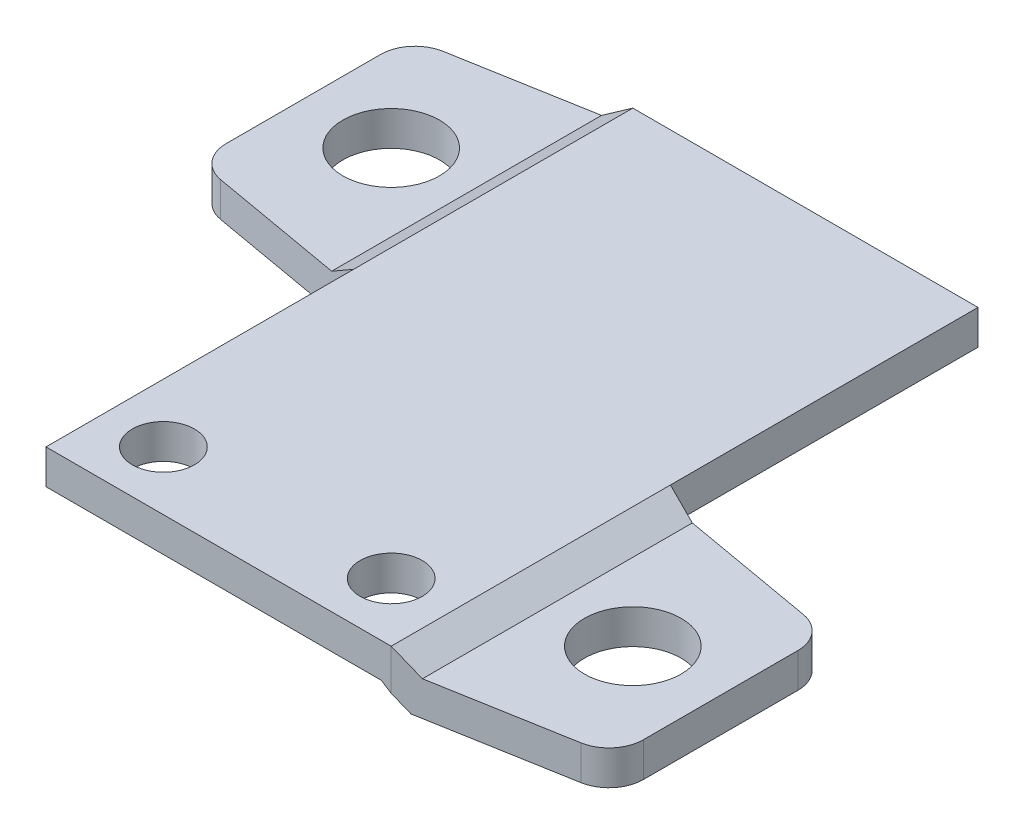
SolidWorks part; units mm, degrees
ref_plane "Front Plane" through (0, 0, 0) normal (0, 0, 1) x (1, 0, 0)
ref_plane "Top Plane" through (0, 0, 0) normal (0, 1, 0) x (1, 0, 0)
ref_plane "Right Plane" through (0, 0, 0) normal (1, 0, 0) x (0, 0, -1)
sketch "Sketch1" plane through (0, 0, 0) normal (0, 0, 1) x (1, 0, 0)
  line L0 (-5, 0) -> (5, 0)
  line L1 (5, 0) -> (5.7699, -0.5)
  line L2 (5.7699, -0.5) -> (10.5, -0.5)
  line L3 (10.5, -0.5) -> (10.5, -1.5)
  line L4 (10.5, -1.5) -> (5.487, -1.5)
  line L5 (5.487, -1.5) -> (4.7171, -1)
  line L6 (4.7171, -1) -> (-4.7171, -1)
  line L7 (-4.7171, -1) -> (-5.487, -1.5)
  line L8 (-5.487, -1.5) -> (-10.5, -1.5)
  line L9 (-10.5, -1.5) -> (-10.5, -0.5)
  line L10 (-10.5, -0.5) -> (-5.7699, -0.5)
  line L11 (-5.7699, -0.5) -> (-5, 0)
  line L12 (0, -1) -> (0, 0) construction
  dimension "D1" = 10
  dimension "D2" = 21
  dimension "D3" = 1
  dimension "D4" = 1
  dimension "D5" = 0.5
  dimension "D6" = 147
  dimension "D7" = 147
  dimension "D8" = 5.013
extrude "Boss-Extrude1" add sketch "Sketch1" along normal mid plane 17
sketch "Sketch2" plane through (0, 0, 0) normal (0, 1, 0) x (1, 0, 0)
  line L0 (5, -8.5) -> (-5, -8.5) construction
  line L1 (-3.3, -6.8) -> (3.3, -6.8) construction
  line L3 (0, 0) -> (0, -6.8) construction
  circle A0 centre (-3.3, -6.8) radius 0.9
  circle A1 centre (3.3, -6.8) radius 0.9
  circle A2 centre (8, -4.5) radius 1.4
  circle A3 centre (-8, 4.5) radius 1.4
  dimension "D1" = 1.8
  dimension "D2" = 2.8
  dimension "D5" = 8
  dimension "D6" = 4.5
  dimension "D3" = 1.7
  dimension "D4" = 6.6
  dimension "D7" = 4.5
  dimension "D8" = 8
extrude "Cut-Extrude1" cut sketch "Sketch2" against normal through all
sketch "Sketch3" plane through (0, 0, 0) normal (0, 1, 0) x (1, 0, 0)
  line L0 (5, -8.5) -> (10.5, -7.5302)
  line L1 (10.5, -8.5) -> (5.7699, -8.5) construction
  line L2 (10.5, -8.5) -> (10.5, 8.5) construction
  line L3 (10.5, -7.5302) -> (10.5, -8.5)
  line L4 (10.5, -8.5) -> (5, -8.5)
  line L6 (10.5, -1.38) -> (5, -0.4102)
  line L7 (5, -0.4102) -> (5, 8.5)
  line L8 (5, 8.5) -> (10.5, 8.5)
  line L9 (10.5, 8.5) -> (10.5, -1.38)
  line L10 (-10.5, 8.5) -> (-5, 8.5)
  line L11 (-5.7699, 8.5) -> (-10.5, 8.5) construction
  line L12 (-5, 8.5) -> (-10.5, 7.5302)
  line L13 (-10.5, -8.5) -> (-10.5, 8.5) construction
  line L14 (-10.5, 7.5302) -> (-10.5, 8.5)
  line L15 (-10.5, 1.38) -> (-5, 0.4102)
  line L16 (-5, 0.4102) -> (-5, -8.5)
  line L17 (-5.7699, -8.5) -> (-10.5, -8.5) construction
  line L18 (-5, -8.5) -> (-10.5, -8.5)
  line L19 (-10.5, -8.5) -> (-10.5, 1.38)
  dimension "D1" = 5.5
  dimension "D2" = 80
  dimension "D3" = 9.88
  dimension "D4" = 80
  dimension "D5" = 5.5
  dimension "D6" = 80
  dimension "D7" = 80
  dimension "D8" = 9.88
extrude "Cut-Extrude2" cut sketch "Sketch3" against normal through all
sketch "Sketch4" plane through (0, 0, 8.5) normal (0, 0, 1) x (1, 0, 0)
  line L0 (-5, -1.1837) -> (-4.7171, -1)
  line L1 (-4.7171, -1) -> (-5, -1)
  line L2 (-5, 0) -> (-5, -1.1837) construction
  line L3 (-5, -1) -> (-5, -1.1837)
extrude "Cut-Extrude3" cut sketch "Sketch4" against normal up to surface (8.8603 mm away)
sketch "Sketch5" plane through (0, 0, -8.5) normal (0, 0, -1) x (-1, 0, 0)
  line L0 (-5, -1.1837) -> (-4.7171, -1)
  line L1 (-4.7171, -1) -> (-5, -1)
  line L2 (-5, -1.1837) -> (-5, 0) construction
  line L3 (-5, -1) -> (-5, -1.1837)
extrude "Cut-Extrude4" cut sketch "Sketch5" against normal up to surface (8.8603 mm away)
fillet "Fillet1" radius 1 4 edges at (10.5, -1, 7.5302) (10.5, -1, 1.38) (-10.5, -1, -1.38) (-10.5, -1, -7.5302)
